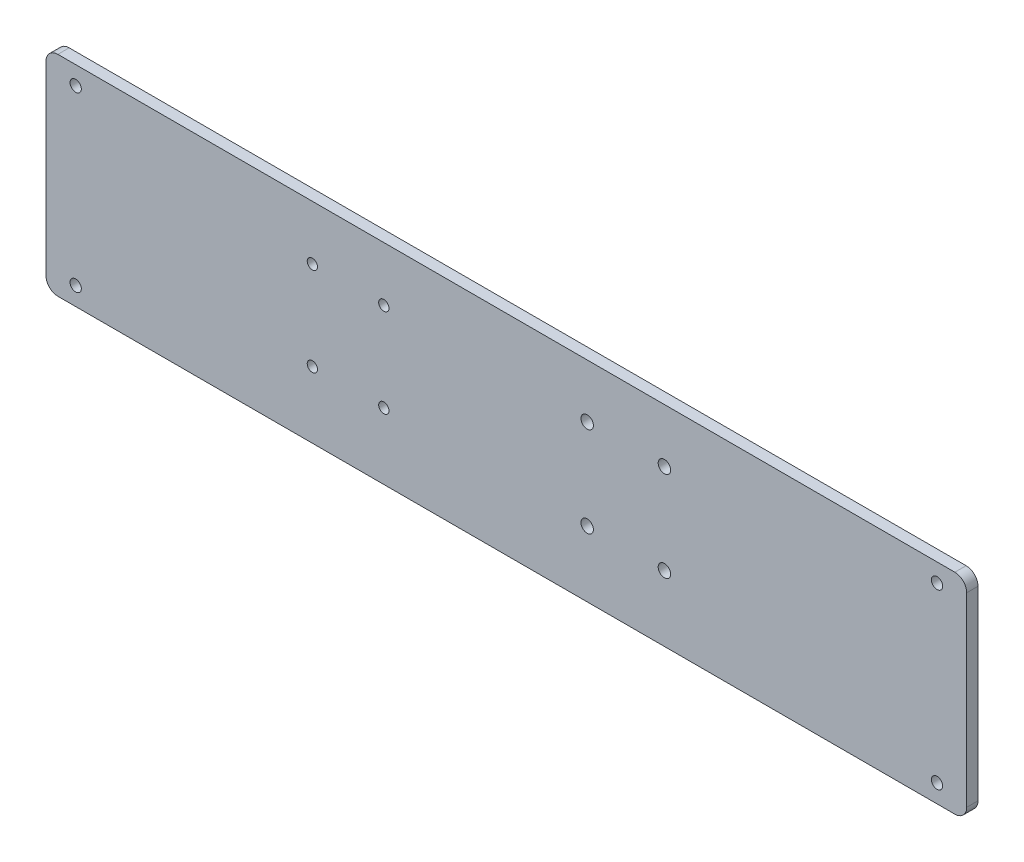
SolidWorks part; units mm, degrees
ref_plane "Front Plane" through (0, 0, 0) normal (0, 0, 1) x (1, 0, 0)
ref_plane "Top Plane" through (0, 0, 0) normal (0, 1, 0) x (1, 0, 0)
ref_plane "Right Plane" through (0, 0, 0) normal (1, 0, 0) x (0, 0, -1)
sketch "Sketch1" plane through (0, 0, 0) normal (0, 0, 1) x (1, 0, 0)
  line L0 (300, -119.1925) -> (294.3567, -119.1925) construction
  line L1 (145, -154.4689) -> (145, -164.7243) construction
  line L2 (-10, -150.4689) -> (-10, -87.9161)
  line L3 (300, -150.4689) -> (300, -87.9161)
  line L4 (-6, -83.9161) -> (296, -83.9161)
  line L5 (-6, -154.4689) -> (296, -154.4689)
  circle A0 centre (172.2123, -102) radius 2.1
  circle A1 centre (290.004, -90.0752) radius 1.9
  circle A2 centre (290.004, -148.3098) radius 1.9
  circle A3 centre (-0.004, -148.3098) radius 1.9
  circle A5 centre (-0.004, -90.0752) radius 1.9
  circle A7 centre (198.2123, -102) radius 2.1
  circle A8 centre (172.2123, -132.35) radius 2.1
  circle A9 centre (198.2123, -132.35) radius 2.1
  circle A10 centre (79.6839, -132.12) radius 1.73
  arc A11 (296, -83.9161) -> (300, -87.9161) centre (296, -87.9161) cw
  arc A12 (296, -154.4689) -> (300, -150.4689) centre (296, -150.4689) ccw
  circle A13 centre (79.6839, -102.23) radius 1.73
  circle A14 centre (103.7439, -102.23) radius 1.73
  circle A15 centre (103.7439, -132.12) radius 1.73
  arc A16 (-6, -154.4689) -> (-10, -150.4689) centre (-6, -150.4689) cw
  arc A17 (-6, -83.9161) -> (-10, -87.9161) centre (-6, -87.9161) ccw
  dimension "D1" = 101.7877
  dimension "D2" = 18.0839
  dimension "D3" = 4.2
extrude "Boss-Extrude1" add sketch "Sketch1" along normal blind 3.8
